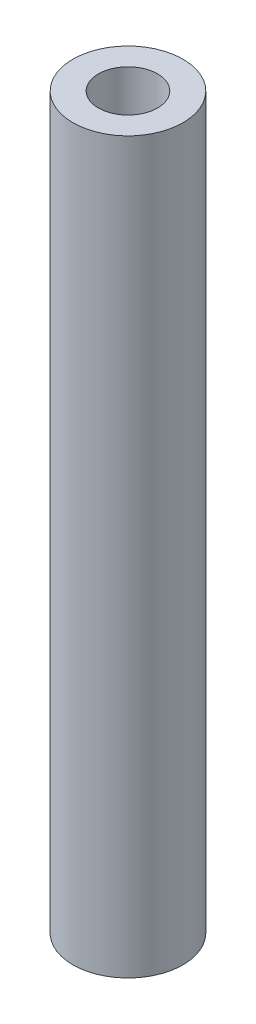
SolidWorks part; units mm, degrees
ref_plane "前视基准面" through (0, 0, 0) normal (0, 0, 1) x (1, 0, 0)
ref_plane "上视基准面" through (0, 0, 0) normal (0, 1, 0) x (1, 0, 0)
ref_plane "右视基准面" through (0, 0, 0) normal (1, 0, 0) x (0, 0, -1)
other "Configuration Table"
sketch "草图1" plane through (0, 0, 0) normal (0, 1, 0) x (1, 0, 0)
  circle A0 centre (0, 0) radius 2.15
  circle A1 centre (0, 0) radius 4
  dimension "D1" = 4.3
  dimension "D2" = 8
extrude "凸台-拉伸1" add sketch "草图1" along normal blind 53
